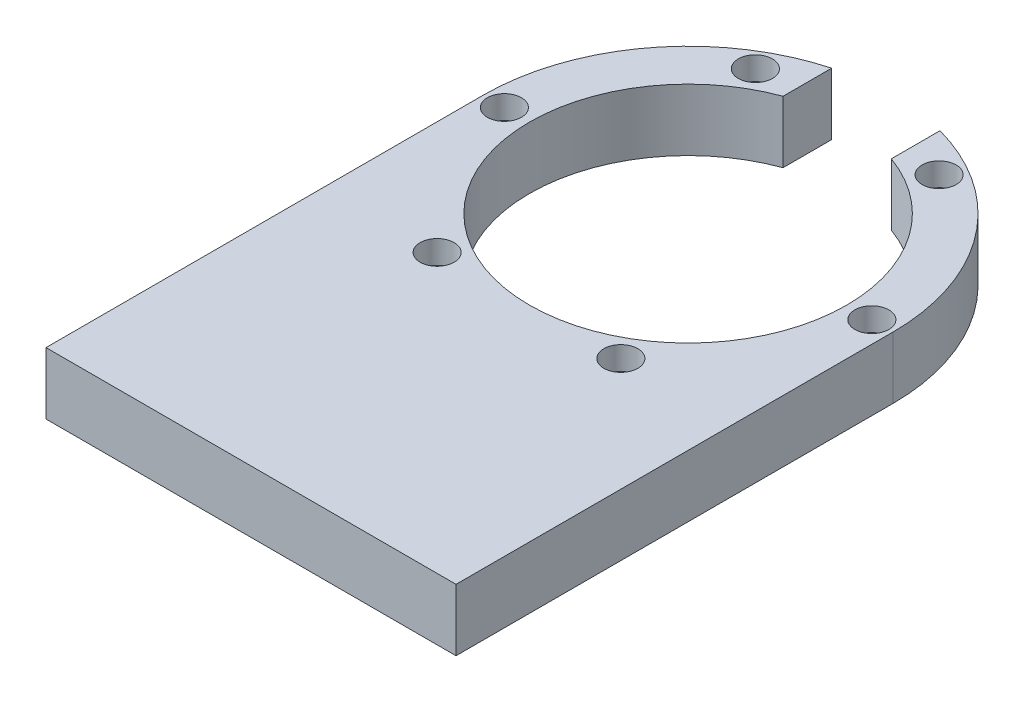
SolidWorks part; units mm, degrees
ref_plane "Front Plane" through (0, 0, 0) normal (0, 0, 1) x (1, 0, 0)
ref_plane "Top Plane" through (0, 0, 0) normal (0, 1, 0) x (1, 0, 0)
ref_plane "Right Plane" through (0, 0, 0) normal (1, 0, 0) x (0, 0, -1)
sketch "Sketch1" plane through (0, 0, 0) normal (0, 1, 0) x (1, 0, 0)
  circle A0 centre (0, 0) radius 26.5
extrude "Boss-Extrude1" add sketch "Sketch1" along normal blind 8
sketch "Sketch2" plane through (0, 8, 0) normal (0, 1, 0) x (1, 0, 0)
  circle A0 centre (0, 0) radius 20.5
extrude "Cut-Extrude1" cut sketch "Sketch2" against normal blind 8 contours A0
sketch "Sketch3" plane through (0, 8, 0) normal (0, 1, 0) x (1, 0, 0)
  line L1 (-7, 27.7229) -> (7, 27.7229)
  line L2 (-7, 27.7229) -> (-7, -1.9802)
  line L3 (-7, -1.9802) -> (7, -1.9802)
  line L4 (7, 27.7229) -> (7, -1.9802)
  dimension "D1" = 14
  dimension "D2" = 7
extrude "Cut-Extrude2" cut sketch "Sketch3" against normal blind 15
sketch "Sketch4" plane through (0, 8, 0) normal (0, 1, 0) x (1, 0, 0)
  line L0 (-26.5, 0) -> (-26.5, -56.5)
  line L1 (-26.5, -56.5) -> (26.5, -56.5)
  line L2 (26.5, 0) -> (26.5, -56.5)
  arc A0 (-7, 25.5588) -> (7, 25.5588) centre (0, 0) ccw construction
  arc A1 (-26.5, 0) -> (26.5, 0) centre (0, 0) ccw
  dimension "D1" = 56.5
extrude "Boss-Extrude2" add sketch "Sketch4" against normal blind 8 contours L0 L1 L2 A1
sketch "Sketch5" plane through (0, 8, 0) normal (0, 1, 0) x (1, 0, 0)
  circle A0 centre (23.75, 0) radius 1.25
  circle A1 centre (11.875, -20.5681) radius 1.25
  circle A2 centre (-11.875, -20.5681) radius 1.25
  circle A3 centre (-23.75, 0) radius 1.25
  circle A4 centre (-11.875, 20.5681) radius 1.25
  circle A5 centre (11.875, 20.5681) radius 1.25
  point P16 (0, 0)
  dimension "D1" = 23.75
  dimension "D2" = 6
extrude "Cut-Extrude3" cut sketch "Sketch5" against normal blind 8
sketch "Sketch6" plane through (0, 8, 0) normal (0, 1, 0) x (1, 0, 0)
  circle A0 centre (23.75, 0) radius 2.2
  circle A1 centre (11.875, -20.5681) radius 2.2
  circle A2 centre (-11.875, -20.5681) radius 2.2
  circle A3 centre (-23.75, 0) radius 2.2
  circle A4 centre (-11.875, 20.5681) radius 2.2
  circle A5 centre (11.875, 20.5681) radius 2.2
  point P16 (0, 0)
  dimension "D1" = 6
extrude "Cut-Extrude4" cut sketch "Sketch6" against normal blind 3
